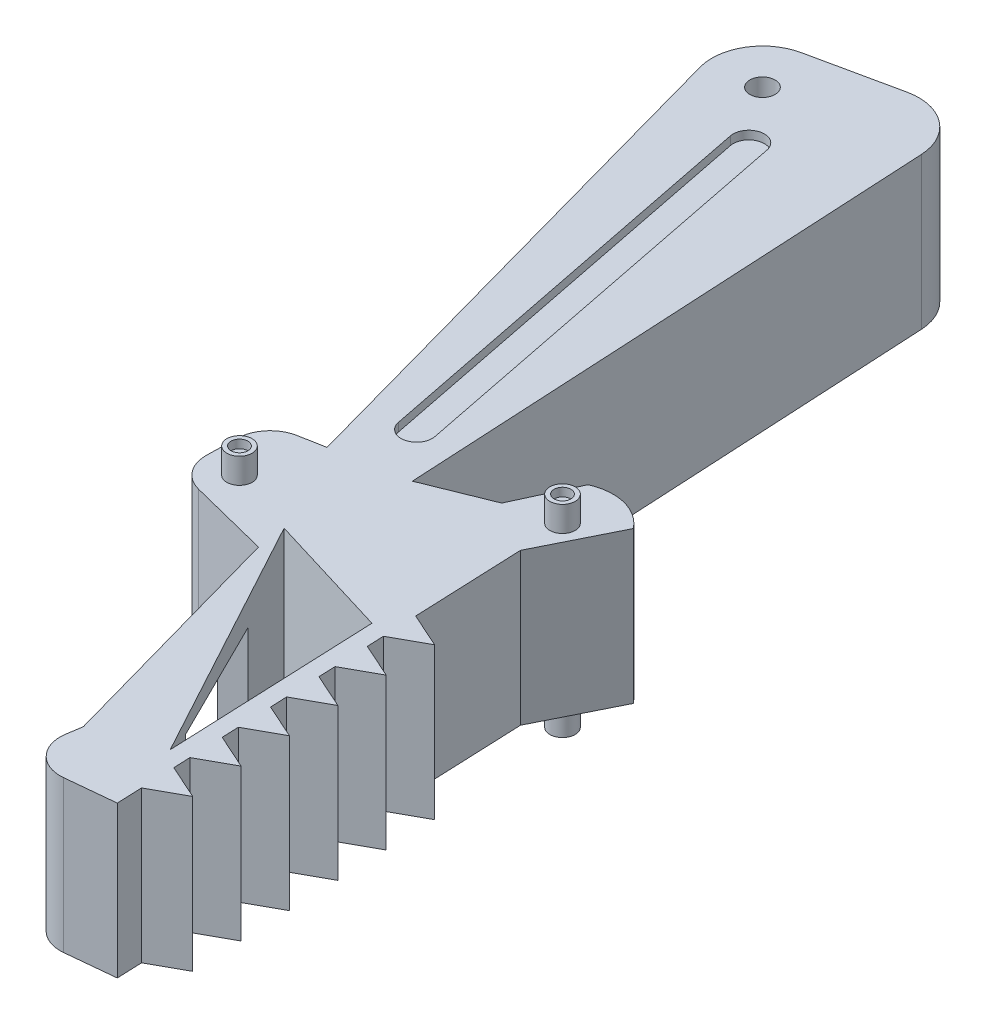
SolidWorks part; units mm, degrees
ref_plane "Front Plane" through (0, 0, 0) normal (0, 0, 1) x (1, 0, 0)
ref_plane "Top Plane" through (0, 0, 0) normal (0, 1, 0) x (1, 0, 0)
ref_plane "Right Plane" through (0, 0, 0) normal (1, 0, 0) x (0, 0, -1)
sketch "Sketch2" plane through (0, 0, 0) normal (0, 1, 0) x (1, 0, 0)
  line L0 (0, 0) -> (-105.2343, -1.055) construction
  line L1 (-43.7753, -0.4388) -> (-67.2427, -5.4672)
  line L2 (-67.2427, -5.4672) -> (-48.5712, -72.9311)
  line L4 (-40.0256, -71.3398) -> (-54.7721, -74.0858)
  line L5 (-54.7721, -74.0858) -> (-54.9923, -84.0833)
  line L6 (-54.9923, -84.0833) -> (-42.3872, -87.2632)
  line L7 (-42.3872, -87.2632) -> (-34.3061, -116.1543)
  line L8 (-34.3061, -116.1543) -> (-35.3743, -123.0723)
  line L9 (-35.3743, -123.0723) -> (-24.4275, -121.9919)
  line L10 (-24.4275, -121.9919) -> (-26.4839, -72.0343)
  line L11 (-26.4839, -72.0343) -> (-22.024, -63.0839)
  line L12 (-43.7753, -0.4388) -> (-40.0256, -71.3398)
  line L13 (-40.0256, -71.3398) -> (-32.4616, -68.2871)
  line L14 (-32.4616, -68.2871) -> (-29.2219, -61.2697)
  arc A0 (-29.2219, -61.2697) -> (-22.024, -63.0839) centre (-26.7752, -66.7481) cw
  dimension "D11" = 6
  dimension "D1" = 70
  dimension "D2" = 71
  dimension "D3" = 24
  dimension "D4" = 15
  dimension "D5" = 10
  dimension "D6" = 13
  dimension "D7" = 30
  dimension "D8" = 7
  dimension "D9" = 11
  dimension "D10" = 50
  dimension "D12" = 10
extrude "Boss-Extrude2" add sketch "Sketch2" along normal mid plane 18 contours A0 L14 L13 L4 L5 L6 L7 L8 L9 L10 L11 | L12 L1 L2 L4
fillet "Fillet2" radius 6 2 edges at (-43.7753, 0, 0.4388) (-67.2427, 0, 5.4672)
fillet "Fillet3" radius 4 3 edges at (-35.3743, 0, 123.0723) (-54.9923, 0, 84.0833) (-54.7721, 0, 74.0858)
sketch "Sketch3" plane through (0, 9, 0) normal (0, 1, 0) x (1, 0, 0)
  line L0 (-24.4275, -121.9919) -> (-24.6333, -116.9919)
  line L1 (-24.4275, -121.9919) -> (-26.4839, -72.0343) construction
  line L2 (-24.6333, -116.9919) -> (-20.6333, -116.8273) construction
  line L3 (-24.551, -118.9919) -> (-24.7157, -114.9919)
  line L4 (-24.7157, -114.9919) -> (-20.6333, -116.8273)
  line L5 (-20.6333, -116.8273) -> (-24.551, -118.9919)
  point P8 (-24.6333, -116.9919)
  line M7 (-24.4275, -121.9919) -> (-26.4839, -72.0343)
  dimension "D1" = 5
  dimension "D2" = 4
  dimension "D3" = 4
extrude "Boss-Extrude3" add sketch "Sketch3" against normal blind 18 contours L2 L4 M7 | L2 L0 L5
pattern_linear "LPattern1" count 6 spacing 6 along (-0.0411, 0, -0.9992) of "Boss-Extrude3"
sketch "Sketch4" plane through (0, 9, 0) normal (0, 1, 0) x (1, 0, 0)
  line L0 (-26.7773, -113.361) -> (-27.8063, -88.361)
  line L1 (-27.8063, -88.361) -> (-42.8063, -83.7975)
  line L2 (-42.8063, -83.7975) -> (-26.7773, -113.361)
  line L3 (-25.2092, -103.0021) -> (-25.2913, -101.0072) construction
  dimension "D1" = 15
  dimension "D2" = 25
extrude "Cut-Extrude1" cut sketch "Sketch4" against normal blind 26
sketch "Sketch5" plane through (-61.9488, 0, 17.3276) normal (-0.963, 0, 0.2694) x (0.2694, 0, 0.963)
  line L0 (79.6198, 6) -> (79.6198, -6)
  line L1 (79.6198, -6) -> (97.6198, -7.5106)
  line L2 (97.6198, -7.5106) -> (97.6198, 7.5106)
  line L3 (97.6198, 7.5106) -> (79.6198, 6)
  line L4 (72.6198, 9) -> (72.6198, -9) construction
  line L5 (72.6198, 9) -> (102.6198, 9) construction
  line L6 (102.6198, 9) -> (102.6198, -9) construction
  point P6 (72.6198, 0)
  point P7 (79.6198, 0)
  point P8 (97.6198, 0)
  dimension "D1" = 3
  dimension "D2" = 5
  dimension "D3" = 7
extrude "Cut-Extrude2" cut sketch "Sketch5" against normal blind 8
sketch "Sketch6" plane through (0, 9, 0) normal (0, 1, 0) x (1, 0, 0)
  circle A0 centre (-59.7624, -10.0006) radius 1.5
  dimension "D1" = 3
extrude "Cut-Extrude3" cut sketch "Sketch6" against normal through all
sketch "Sketch7" plane through (0, 9, 0) normal (0, 1, 0) x (1, 0, 0)
  circle A0 centre (-26.7752, -66.7481) radius 1.5
  circle A1 centre (-50.9231, -80.9846) radius 1.5
  dimension "D1" = 3
extrude "Boss-Extrude4" add sketch "Sketch7" along normal blind 3
sketch "Sketch8" plane through (0, 12, 0) normal (0, 1, 0) x (1, 0, 0)
  circle A2 centre (-50.9231, -80.9846) radius 1
  circle A3 centre (-50.9231, -80.9846) radius 1
  dimension "D1" = 0.5
extrude "Cut-Extrude4" cut sketch "Sketch8" against normal blind 1
sketch "Sketch9" plane through (0, 12, 0) normal (0, 1, 0) x (1, 0, 0)
  circle A2 centre (-26.7752, -66.7481) radius 1
  circle A3 centre (-26.7752, -66.7481) radius 1
  dimension "D1" = 0.5
extrude "Cut-Extrude5" cut sketch "Sketch9" against normal blind 1
sketch "Sketch10" plane through (0, 9, 0) normal (0, 1, 0) x (1, 0, 0)
  line L0 (-54.8479, -16.5441) -> (-45.0892, -65.7654) construction
  line L1 (-53.0321, -16.1842) -> (-43.2735, -65.4054)
  line L2 (-56.6636, -16.9041) -> (-46.905, -66.1254)
  arc A0 (-53.0321, -16.1842) -> (-56.6636, -16.9041) centre (-54.8479, -16.5441) ccw
  arc A1 (-46.905, -66.1254) -> (-43.2735, -65.4054) centre (-45.0892, -65.7654) ccw
  point P2 (-49.9685, -41.1548)
extrude "Cut-Extrude6" cut sketch "Sketch10" against normal blind 1
mirror "Mirror1" about plane through (0, 0, 0) normal (0, 1, 0) of "Cut-Extrude6", "Cut-Extrude5", "Cut-Extrude4", "Boss-Extrude4"
